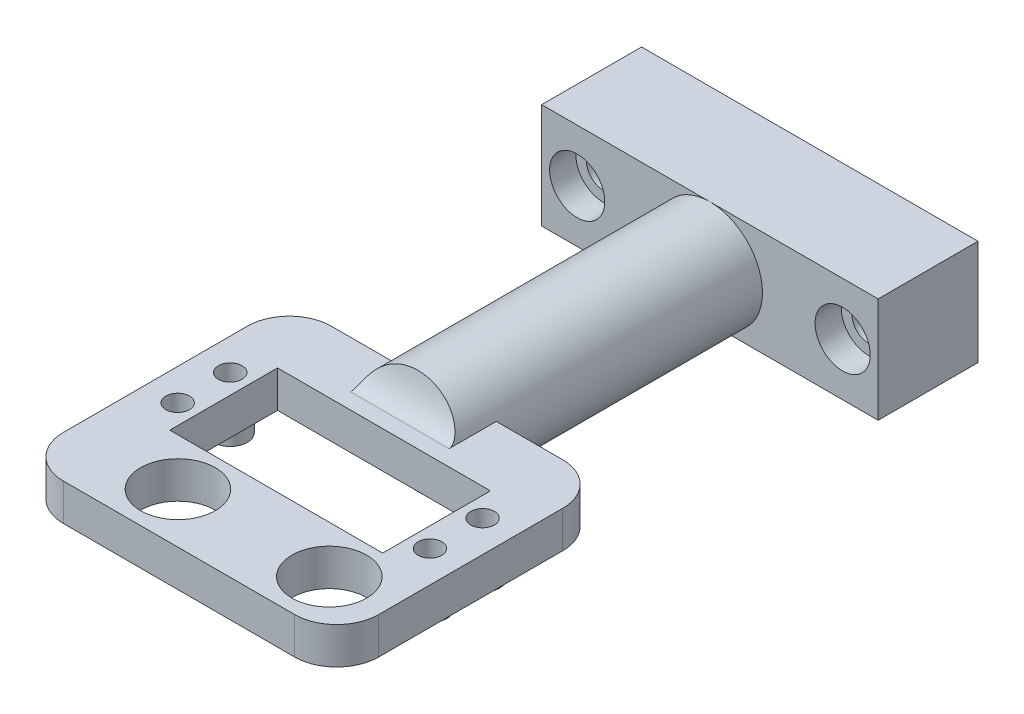
SolidWorks part; units mm, degrees
ref_plane "Front Plane" through (0, 0, 0) normal (0, 0, 1) x (1, 0, 0)
ref_plane "Top Plane" through (0, 0, 0) normal (0, 1, 0) x (1, 0, 0)
ref_plane "Right Plane" through (0, 0, 0) normal (1, 0, 0) x (0, 0, -1)
sketch "Sketch1" plane through (0, 0, 0) normal (0, 1, 0) x (1, 0, 0)
  line L0 (-9.75, 7.75) -> (-9.75, -11.45) construction
  line L1 (-30, -21) -> (30, -21)
  line L2 (-30, -21) -> (-30, 21)
  line L3 (-30, 21) -> (30, 21)
  line L4 (30, -21) -> (30, 21)
  line L5 (0, 21) -> (0, -21) construction
  line L6 (-30, 0) -> (30, 0) construction
  line L7 (-20.25, -2.5) -> (20.25, -2.5)
  line L8 (-20.25, -2.5) -> (-20.25, 18)
  line L9 (-20.25, 18) -> (20.25, 18)
  line L10 (20.25, -2.5) -> (20.25, 18)
  line L11 (0, 18) -> (0, -2.5) construction
  line L12 (-20.25, 7.75) -> (20.25, 7.75) construction
  line L13 (-9.75, -11.45) -> (19.05, -11.45) construction
  line L14 (24, 12.75) -> (24, 2.75) construction
  line L15 (20.25, 7.75) -> (30, 7.75) construction
  circle A0 centre (-9.75, -11.45) radius 7.1
  circle A1 centre (19.05, -11.45) radius 7.1
  circle A2 centre (24, 12.75) radius 2.25
  circle A3 centre (24, 2.75) radius 2.25
  circle A4 centre (-24, 2.75) radius 2.25
  circle A5 centre (-24, 12.75) radius 2.25
  point P0 (0, 0)
  point P4 (0, 7.75)
  point P17 (24, 7.75)
  dimension "D7" = 4.5
  dimension "D8" = 4.5
  dimension "D12" = 14.2
  dimension "D13" = 14.2
  dimension "D1" = 40.5
  dimension "D2" = 20.5
  dimension "D3" = 3
  dimension "D4" = 19.2
  dimension "D5" = 28.8
  dimension "D6" = 60
  dimension "D9" = 10
  dimension "D10" = 24
  dimension "D11" = 42
  dimension "D14" = 30
extrude "Boss-Extrude1" add sketch "Sketch1" along normal blind 7
sketch "Sketch2" plane through (0, 0, 0) normal (0, -1, 0) x (1, 0, 0)
  line L5 (0, -1000) -> (0, 49000) construction
  circle A0 centre (24, -2.75) radius 3.25
  circle A1 centre (24, -12.75) radius 3.25
  circle A2 centre (24, -12.75) radius 2.25 construction
  circle A3 centre (24, -2.75) radius 2.25 construction
  circle A4 centre (24, -12.75) radius 2.25
  circle A5 centre (24, -2.75) radius 2.25
  circle A6 centre (-24, -12.75) radius 3.25
  circle A7 centre (-24, -12.75) radius 2.25
  circle A8 centre (-24, -2.75) radius 3.25
  circle A9 centre (-24, -2.75) radius 2.25
  dimension "D1" = 6.5
  dimension "D2" = 6.5
extrude "Boss-Extrude2" add sketch "Sketch2" along normal blind 2.9
sketch "Sketch3" plane through (0, 0, -21) normal (0, 0, -1) x (-1, 0, 0)
  line L0 (-30, 3.5) -> (30, 3.5) construction
  line L4 (-30, 0) -> (30, 0)
  line L5 (30, 0) -> (30, 7)
  line L6 (30, 7) -> (-30, 7)
  line L7 (-30, 7) -> (-30, 0)
  line L8 (-30, 0) -> (30, 0)
  line L9 (30, 0) -> (30, 7)
  line L10 (30, 7) -> (-30, 7)
  line L11 (-30, 7) -> (-30, 0)
  circle A3 centre (0, 3.5) radius 10
  dimension "D2" = 20
  dimension "D1" = 0
extrude "Boss-Extrude3" add sketch "Sketch3" along normal blind 9
sketch "Sketch4" plane through (-30, 0, 0) normal (-1, 0, 0) x (0, 0, 1)
  line L0 (-25, 20.02) -> (-17, 20.02) construction
  line L1 (-30, 3.5) -> (21, 3.5) construction
  line L4 (-30, 7) -> (21, 7) construction
  line L9 (-30, 0) -> (21, 0)
  line L10 (21, 0) -> (21, 7)
  line L11 (21, 7) -> (-30, 7)
  line L12 (-30, 7) -> (-30, 0)
  line L13 (-30, 0) -> (21, 0)
  line L14 (21, 0) -> (21, 7)
  line L15 (21, 7) -> (-30, 7)
  line L16 (-30, 7) -> (-30, 0)
  ellipse E0 centre (-21, 20.02) end of major axis (-21, 7) minor radius 4
  ellipse E1 centre (-21, -13.02) end of major axis (-21, 0) minor radius 4
  dimension "D1" = 0
  dimension "D2" = 26.04
  dimension "D3" = 8
  dimension "D4" = 5
extrude "Cut-Extrude1" cut sketch "Sketch4" against normal through all contours E0 | E1
fillet "Fillet1" radius 8 4 edges at (-30, 3.5, 21) (30, 3.5, 21) (30, 3.5, -30) (-30, 3.5, -30)
sketch "Sketch5" plane through (0, 0, -30) normal (0, 0, -1) x (-1, 0, 0)
  arc A0 (9.3675, 7) -> (-9.3675, 7) centre (0, 3.5) ccw construction
  arc A1 (9.3675, 7) -> (-9.3675, 7) centre (0, 3.5) ccw
  circle A2 centre (0, 3.5) radius 10
  arc M5 (9.3675, 7) -> (-9.3675, 7) centre (0, 3.5) ccw
  arc M9 (-9.3675, 0) -> (9.3675, 0) centre (0, 3.5) ccw
extrude "Boss-Extrude4" add sketch "Sketch5" along normal blind 50 contours A2 M5 M9
sketch "Sketch6" plane through (0, 0, -80) normal (0, 0, -1) x (-1, 0, 0)
  line L1 (-32, -6.5) -> (32, -6.5)
  line L2 (-32, -6.5) -> (-32, 13.5)
  line L3 (-32, 13.5) -> (32, 13.5)
  line L4 (32, -6.5) -> (32, 13.5)
  line L5 (0, 13.5) -> (0, -6.5) construction
  line L6 (-32, 3.5) -> (32, 3.5) construction
  circle A0 centre (0, 3.5) radius 10 construction
  circle A1 centre (0, 3.5) radius 10 construction
  circle A2 centre (-25.25, 3.5) radius 3.25
  circle A3 centre (25.25, 3.5) radius 3.25
  dimension "D3" = 6.5
  dimension "D1" = 25.25
  dimension "D2" = 64
  dimension "D4" = 20
extrude "Boss-Extrude5" add sketch "Sketch6" along normal blind 19
sketch "Sketch7" plane through (0, 0, -80) normal (0, 0, 1) x (1, 0, 0)
  circle A0 centre (25.25, 3.5) radius 3.25 construction
  circle A1 centre (25.25, 3.5) radius 3.25
  circle A2 centre (-25.25, 3.5) radius 3.25 construction
  circle A3 centre (-25.25, 3.5) radius 3.25
  circle A4 centre (25.25, 3.5) radius 5.25
  circle A5 centre (-25.25, 3.5) radius 5.25
  dimension "D1" = 10.5
  dimension "D2" = 10.5
extrude "Cut-Extrude2" cut sketch "Sketch7" against normal blind 5
